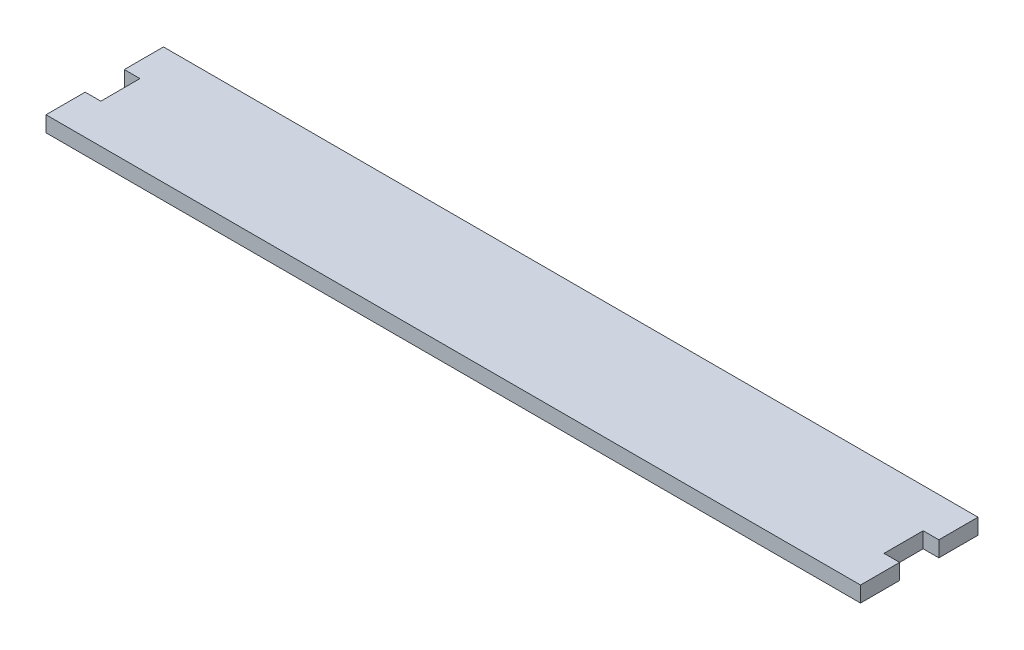
SolidWorks part; units mm, degrees
ref_plane "Front Plane" through (0, 0, 0) normal (0, 0, 1) x (1, 0, 0)
ref_plane "Top Plane" through (0, 0, 0) normal (0, 1, 0) x (1, 0, 0)
ref_plane "Right Plane" through (0, 0, 0) normal (1, 0, 0) x (0, 0, -1)
sketch "Sketch1" plane through (0, 0, 0) normal (0, 1, 0) x (1, 0, 0)
  line L1 (0, 0) -> (200, 0)
  line L2 (0, 10) -> (0, 20)
  line L3 (0, 30) -> (200, 30)
  line L4 (200, 10) -> (200, 20)
  line L5 (200, 10) -> (204, 10)
  line L6 (200, 10) -> (200, 20)
  line L7 (200, 20) -> (204, 20)
  line L9 (0, 10) -> (-4, 10)
  line L10 (0, 10) -> (0, 20)
  line L11 (0, 20) -> (-4, 20)
  line L13 (0, 30) -> (-4, 30)
  line L15 (0, 20) -> (-4, 20)
  line L16 (-4, 30) -> (-4, 20)
  line L17 (0, 0) -> (-4, 0)
  line L19 (0, 10) -> (-4, 10)
  line L20 (-4, 0) -> (-4, 10)
  line L21 (200, 0) -> (204, 0)
  line L23 (200, 10) -> (204, 10)
  line L24 (204, 0) -> (204, 10)
  line L25 (200, 30) -> (204, 30)
  line L27 (200, 20) -> (204, 20)
  line L28 (204, 30) -> (204, 20)
  dimension "D1" = 200
  dimension "D2" = 4
  dimension "D3" = 10
  dimension "D4" = 10
  dimension "D5" = 10
  dimension "D6" = 10
  dimension "D7" = 10
  dimension "D8" = 4
extrude "Boss-Extrude2" add sketch "Sketch1" along normal blind 4 contours L28 L25 L3 L13 L16 L11 L2 L9 L20 L17 L1 L21 L24 L5 L4 L7
